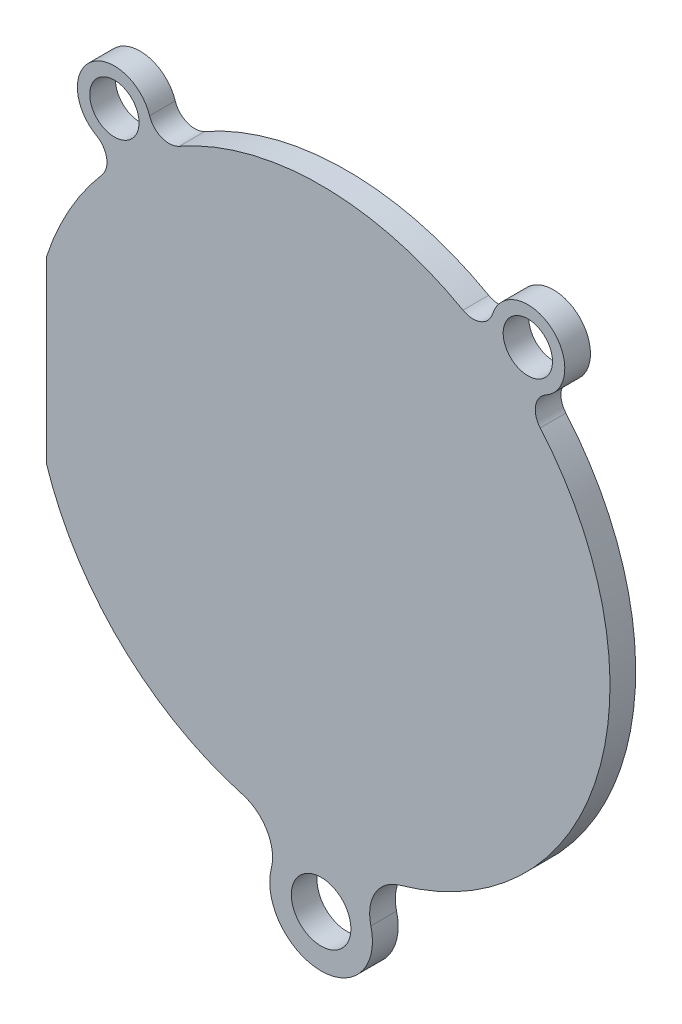
SolidWorks part; units mm, degrees
ref_plane "Front Plane" through (0, 0, 0) normal (0, 0, 1) x (1, 0, 0)
ref_plane "Top Plane" through (0, 0, 0) normal (0, 1, 0) x (1, 0, 0)
ref_plane "Right Plane" through (0, 0, 0) normal (1, 0, 0) x (0, 0, -1)
sketch "Sketch1" plane through (0, 0, 0) normal (0, 0, 1) x (1, 0, 0)
  line L7 (-16.9841, -5.5245) -> (-16.9841, 5.5245)
  arc A0 (-13.5462, 11.6395) -> (-13.8916, 13.5768) centre (-14.5094, 12.4672) ccw construction
  arc A1 (4.8506, -17.1887) -> (13.5462, 11.6395) centre (0, 0) ccw construction
  arc A2 (8.7709, 15.5579) -> (-8.7709, 15.5579) centre (0, 0) ccw construction
  arc A3 (4.8506, -17.1887) -> (3.078, -20.2562) centre (5.5404, -19.6332) ccw construction
  arc A4 (13.8916, 13.5768) -> (13.5462, 11.6395) centre (14.5094, 12.4672) ccw construction
  arc A5 (8.7709, 15.5579) -> (10.6034, 16.2749) centre (9.3946, 16.6642) ccw construction
  arc A6 (-3.078, -20.2562) -> (-4.8506, -17.1887) centre (-5.5404, -19.6332) ccw construction
  arc A7 (-13.5462, 11.6395) -> (-16.9841, 5.5245) centre (0, 0) ccw
  arc A8 (-16.9841, -5.5245) -> (-4.8506, -17.1887) centre (0, 0) ccw
  arc A9 (-3.078, -20.2562) -> (3.078, -20.2562) centre (0, -21.035) ccw construction
  arc A10 (4.8506, -17.1887) -> (13.5462, 11.6395) centre (0, 0) ccw
  arc A11 (-3.078, -20.2562) -> (-4.8506, -17.1887) centre (-5.5404, -19.6332) ccw
  arc A12 (8.7709, 15.5579) -> (-8.7709, 15.5579) centre (0, 0) ccw
  arc A13 (-3.078, -20.2562) -> (3.078, -20.2562) centre (0, -21.035) ccw
  arc A14 (4.8506, -17.1887) -> (3.078, -20.2562) centre (5.5404, -19.6332) ccw
  circle A15 centre (0, -21.035) radius 1.8415 construction
  circle A17 centre (0, -21.035) radius 1.8415
  arc A18 (-10.6034, 16.2749) -> (-13.8916, 13.5768) centre (-12.7793, 15.574) ccw construction
  circle A19 centre (-12.7793, 15.574) radius 1.524 construction
  arc A20 (-10.6034, 16.2749) -> (-8.7709, 15.5579) centre (-9.3946, 16.6642) ccw construction
  arc A22 (-13.5462, 11.6395) -> (-13.8916, 13.5768) centre (-14.5094, 12.4672) ccw
  arc A23 (-10.6034, 16.2749) -> (-13.8916, 13.5768) centre (-12.7793, 15.574) ccw
  circle A24 centre (-12.7793, 15.574) radius 1.524
  arc A25 (-10.6034, 16.2749) -> (-8.7709, 15.5579) centre (-9.3946, 16.6642) ccw
  arc A26 (13.8916, 13.5768) -> (10.6034, 16.2749) centre (12.7793, 15.574) ccw construction
  circle A27 centre (12.7793, 15.574) radius 1.524 construction
  arc A28 (13.8916, 13.5768) -> (10.6034, 16.2749) centre (12.7793, 15.574) ccw
  circle A29 centre (12.7793, 15.574) radius 1.524
  arc A30 (8.7709, 15.5579) -> (10.6034, 16.2749) centre (9.3946, 16.6642) ccw
  arc A31 (13.8916, 13.5768) -> (13.5462, 11.6395) centre (14.5094, 12.4672) ccw
extrude "Boss-Extrude1" add sketch "Sketch1" along normal blind 1.5875
